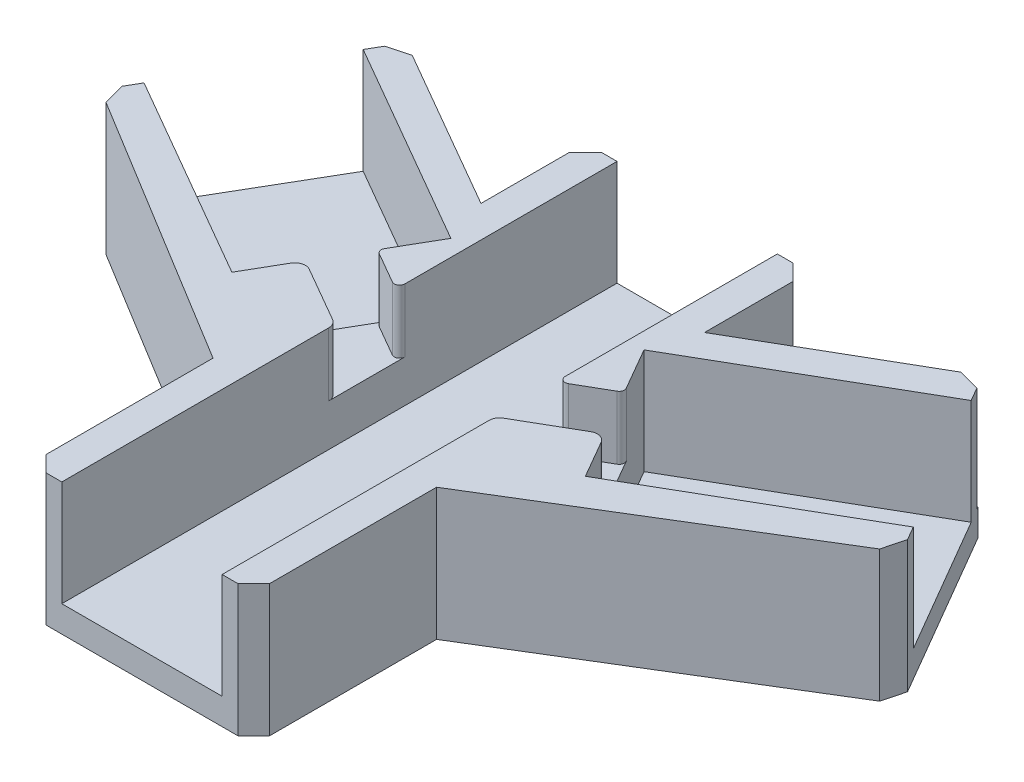
SolidWorks part; units mm, degrees
ref_plane "Front" through (0, 0, 0) normal (0, 0, 1) x (1, 0, 0)
ref_plane "Top" through (0, 0, 0) normal (0, 1, 0) x (1, 0, 0)
ref_plane "Right" through (0, 0, 0) normal (1, 0, 0) x (0, 0, -1)
sketch "Эскиз1" plane through (0, 0, 0) normal (0, 1, 0) x (1, 0, 0)
  line L0 (0, 0) -> (0, 90) construction
  line L1 (0, 0) -> (100.7423, 58.1636) construction
  line L2 (0, 0) -> (-100.7423, 58.1636) construction
  line L3 (93.1423, 45) -> (15.2, 0) construction
  line L4 (93.1423, 45) -> (85.5423, 58.1636) construction
  line L5 (15.2, 0) -> (7.6, 13.1636) construction
  line L6 (85.5423, 58.1636) -> (7.6, 13.1636) construction
  line L7 (93.1423, 45) -> (7.6, 13.1636) construction
  line L8 (15.2, 0) -> (85.5423, 58.1636) construction
  line L9 (-7.6, 90) -> (-7.6, -180) construction
  line L10 (-7.6, 90) -> (7.6, 90) construction
  line L11 (-7.6, -180) -> (7.6, -180) construction
  line L12 (7.6, 90) -> (7.6, -180) construction
  line L13 (-7.6, 90) -> (7.6, -180) construction
  line L14 (-7.6, -180) -> (7.6, 90) construction
  line L15 (-85.5423, 58.1636) -> (-7.6, 13.1636) construction
  line L16 (-85.5423, 58.1636) -> (-93.1423, 45) construction
  line L17 (-7.6, 13.1636) -> (-15.2, 0) construction
  line L18 (-93.1423, 45) -> (-15.2, 0) construction
  line L19 (-85.5423, 58.1636) -> (-15.2, 0) construction
  line L20 (-7.6, 13.1636) -> (-93.1423, 45) construction
  line L21 (-50.3711, 29.0818) -> (-46.2985, 36.1358) construction
  line L22 (0, -45) -> (-9.1217, -45) construction
  line L23 (50.3711, 29.0818) -> (42.3504, 42.9741) construction
  line L24 (-7.6, 13.1636) -> (-7.6, 28.2617)
  line L26 (-10.6, 28.2617) -> (-10.6, 18.3597)
  line L27 (-10.6, 18.3597) -> (-27.7506, 28.2617)
  line L28 (-27.7506, 28.2617) -> (-29.2506, 25.6636)
  line L29 (-29.2506, 25.6636) -> (-7.6, 13.1636)
  line L30 (-29.2506, 25.6636) -> (-36.8506, 12.5) construction
  line L31 (-36.8506, 12.5) -> (-7.6, -4.3879)
  line L32 (-36.8506, 12.5) -> (-38.4144, 9.9398)
  line L33 (-38.4144, 9.9398) -> (-10.6, -7.0489)
  line L34 (-10.6, -7.0489) -> (-10.6, -24.3879)
  line L35 (-10.6, -24.3879) -> (-7.6, -24.3879)
  line L36 (-7.6, -24.3879) -> (-7.6, -4.3879)
  line L37 (7.6, -24.3879) -> (7.6, -4.3879)
  line L38 (10.6, -24.3879) -> (7.6, -24.3879)
  line L39 (10.6, -7.0489) -> (10.6, -24.3879)
  line L40 (38.4144, 9.9398) -> (10.6, -7.0489)
  line L41 (36.8506, 12.5) -> (38.4144, 9.9398)
  line L42 (36.8506, 12.5) -> (7.6, -4.3879)
  line L43 (29.2506, 25.6636) -> (7.6, 13.1636)
  line L44 (27.7506, 28.2617) -> (29.2506, 25.6636)
  line L45 (10.6, 18.3597) -> (27.7506, 28.2617)
  line L46 (10.6, 28.2617) -> (10.6, 18.3597)
  line L48 (7.6, 13.1636) -> (7.6, 28.2617)
  line L49 (-10.6, 28.2617) -> (-7.6, 28.2617)
  line L50 (7.6, 28.2617) -> (10.6, 28.2617)
  point P6 (50.3711, 29.0818)
  point P7 (0, -45)
  point P8 (-50.3711, 29.0818)
  dimension "D5" = 90
  dimension "D9" = 90
  dimension "D10" = 270
  dimension "D12" = 3
  dimension "D14" = 25
  dimension "D15" = 3
  dimension "D16" = 3
  dimension "D17" = 20
extrude "Бобышка-Вытянуть1" add sketch "Эскиз1" along normal blind 10
sketch "Эскиз2" plane through (0, 0, 0) normal (0, -1, 0) x (1, 0, 0)
  line L0 (-10.6, 24.3879) -> (10.6, 24.3879)
  line L1 (10.6, 24.3879) -> (10.6, 7.0489)
  line L2 (10.6, 7.0489) -> (38.4144, -9.9398)
  line L3 (38.4144, -9.9398) -> (27.7506, -28.2617)
  line L9 (-27.7506, -28.2617) -> (-38.4144, -9.9398)
  line L10 (-38.4144, -9.9398) -> (-10.6, 7.0489)
  line L11 (-10.6, 7.0489) -> (-10.6, 24.3879)
  line L14 (-27.7506, -28.2617) -> (27.7506, -28.2617)
extrude "Бобышка-Вытянуть2" add sketch "Эскиз2" along normal blind 2.5
sketch "Эскиз3" plane through (0, 0, 0) normal (0, 1, 0) x (1, 0, 0)
  line L0 (9.1588, 14.0636) -> (16.7588, 0.9)
  line L1 (7.6, 13.1636) -> (29.2506, 25.6636) construction
  line L2 (36.8506, 12.5) -> (7.6, -4.3879) construction
  line L3 (16.7588, 0.9) -> (7.6, -4.3879)
  line L4 (7.6, -4.3879) -> (7.6, 13.1636)
  line L5 (0, 0) -> (0, 22.3371) construction
  line L6 (-7.6, -4.3879) -> (-7.6, 13.1636)
  line L7 (-16.7588, 0.9) -> (-7.6, -4.3879)
  line L8 (-9.1588, 14.0636) -> (-16.7588, 0.9)
  line L9 (9.1588, 14.0636) -> (7.6, 13.1636)
  line L10 (-9.1588, 14.0636) -> (-7.6, 13.1636)
  dimension "D1" = 1.8
extrude "Бобышка-Вытянуть3" add sketch "Эскиз3" along normal blind 10
sketch "Эскиз4" plane through (0, 10, 0) normal (0, 1, 0) x (1, 0, 0)
  line L0 (0, 0) -> (17.6479, 10.189) construction
  line L1 (0, 0) -> (-17.8534, 10.3077) construction
  line L2 (-15.8872, 6.2857) -> (-6.6289, 0.9404)
  line L3 (-15.8872, 6.2857) -> (-13.3872, 10.6159)
  line L4 (-6.6289, 0.9404) -> (-4.1289, 5.2706)
  line L5 (-13.3872, 10.6159) -> (-4.1289, 5.2706)
  line L6 (-15.8872, 6.2857) -> (-4.1289, 5.2706) construction
  line L7 (-6.6289, 0.9404) -> (-13.3872, 10.6159) construction
  line L8 (14.0084, 10.9745) -> (3.5077, 4.9119)
  line L9 (14.0084, 10.9745) -> (16.5084, 6.6444)
  line L10 (3.5077, 4.9119) -> (6.0077, 0.5818)
  line L11 (16.5084, 6.6444) -> (6.0077, 0.5818)
  line L12 (14.0084, 10.9745) -> (6.0077, 0.5818) construction
  line L13 (3.5077, 4.9119) -> (16.5084, 6.6444) construction
  point P5 (-10.0081, 5.7782)
  point P6 (10.0081, 5.7782)
  dimension "D1" = 5
  dimension "D2" = 5
  dimension "D3" = 2.5
  dimension "D4" = 2.5
extrude "Вырез-Вытянуть1" cut sketch "Эскиз4" against normal blind 6
fillet "Скругление4" radius 1 4 edges at (14.2088, 7, -5.3167) (7.6, 7, -1.5011) (-14.2088, 7, -5.3167) (-7.6, 7, -1.5011)
fillet "Скругление5" radius 0.5 4 edges at (11.7088, 7, -9.6469) (7.6, 7, -7.2746) (-7.6, 7, -7.2746) (-11.7088, 7, -9.6469)
sketch "Эскиз5" plane through (0, 10, 0) normal (0, 1, 0) x (1, 0, 0)
  line L0 (-24.047, 33.631) -> (-39.8329, 6.5086)
  line L1 (24.284, 33.2239) -> (39.7032, 6.7314)
  line L2 (-38.4144, 9.9398) -> (-27.7506, 28.2617) construction
  line L3 (27.7506, 28.2617) -> (38.4144, 9.9398) construction
  line L4 (-24.047, 33.631) -> (-28.6154, 34.9788)
  line L5 (-28.6154, 34.9788) -> (-44.7567, 10.7275)
  line L6 (-44.7567, 10.7275) -> (-39.8329, 6.5086)
  line L7 (24.284, 33.2239) -> (29.8082, 34.3049)
  line L8 (29.8082, 34.3049) -> (44.2995, 9.4066)
  line L9 (44.2995, 9.4066) -> (39.7032, 6.7314)
  dimension "D1" = 0.5
  dimension "D2" = 0.5
extrude "Вырез-Вытянуть2" cut sketch "Эскиз5" against normal through all
chamfer "Фаска1" distance 1.5 angle 45 8 edges at (-10.6, 3.75, 24.3879) (10.6, 3.75, 24.3879) (-37.9876, 3.75, -9.6791) (-27.3176, 5, -28.0117) (-10.6, 5, -28.2617) (10.6, 5, -28.2617) (27.3176, 5, -28.0117) (37.9876, 3.75, -9.6791)
chamfer "Фаска2" distance 1.5 angle 45 2 edges at (27.1721, -1.25, -28.2617) (-27.1721, -1.25, -28.2617)
